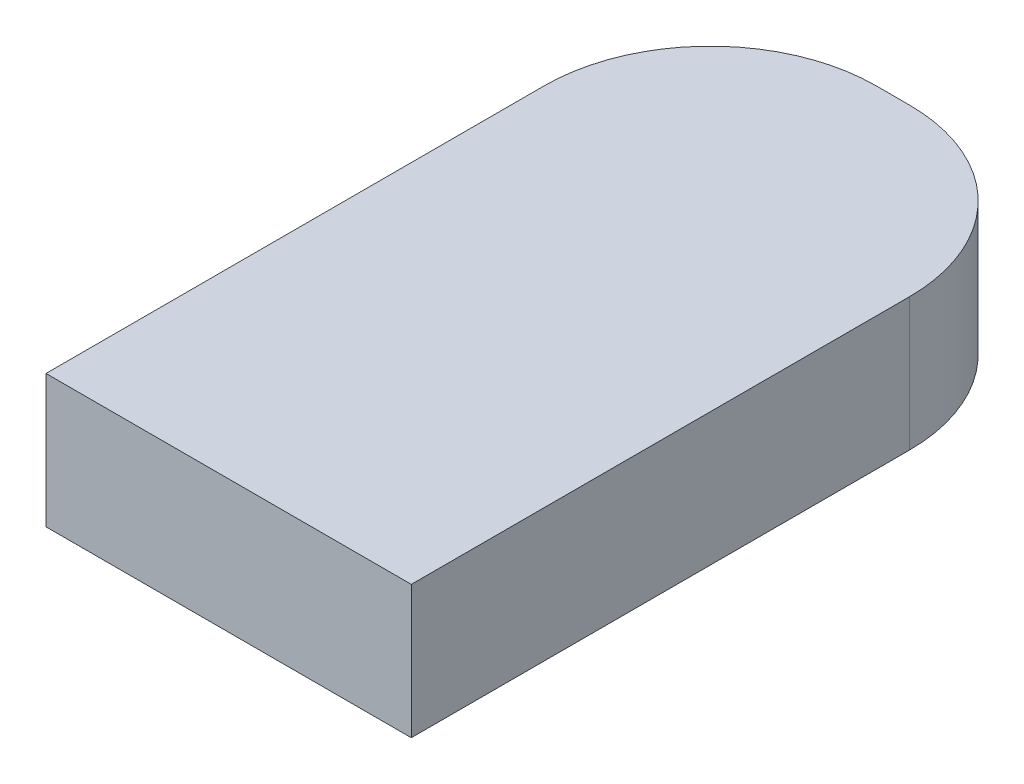
SolidWorks part; units mm, degrees
ref_plane "Front Plane" through (0, 0, 0) normal (0, 0, 1) x (1, 0, 0)
ref_plane "Top Plane" through (0, 0, 0) normal (0, 1, 0) x (1, 0, 0)
ref_plane "Right Plane" through (0, 0, 0) normal (1, 0, 0) x (0, 0, -1)
sketch "Sketch1" plane through (0, 0, 0) normal (0, 1, 0) x (1, 0, 0)
  line L1 (0, 0) -> (22, 0)
  line L2 (0, 0) -> (0, 30)
  line L3 (10, 40) -> (12, 40)
  line L4 (22, 0) -> (22, 30)
  arc A0 (12, 40) -> (22, 30) centre (12, 30) cw
  arc A1 (0, 30) -> (10, 40) centre (10, 30) cw
  point P7 (22, 40)
  dimension "D3" = 10
  dimension "D1" = 22
  dimension "D2" = 40
extrude "Boss-Extrude1" add sketch "Sketch1" along normal blind 8
